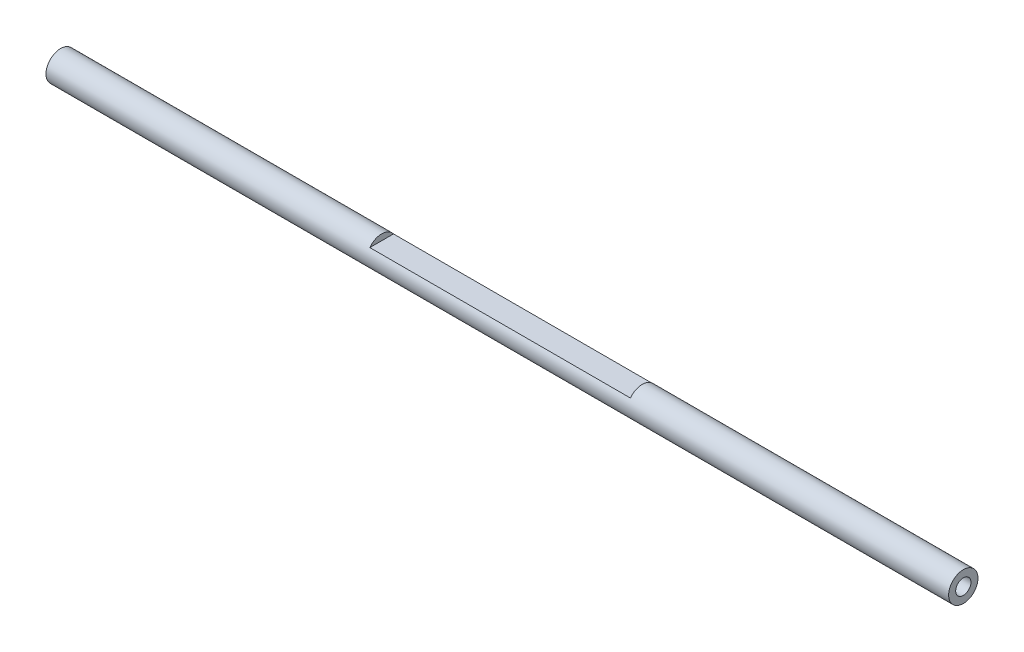
SolidWorks part; units mm, degrees
ref_plane "Front Plane" through (0, 0, 0) normal (0, 0, 1) x (1, 0, 0)
ref_plane "Top Plane" through (0, 0, 0) normal (0, 1, 0) x (1, 0, 0)
ref_plane "Right Plane" through (0, 0, 0) normal (1, 0, 0) x (0, 0, -1)
sketch "Sketch1" plane through (0, 0, 0) normal (1, 0, 0) x (0, 0, -1)
  line L1 (10, 8.45) -> (-10, 8.45)
  line L2 (10, 8.45) -> (10, -8.45)
  line L3 (10, -8.45) -> (-10, -8.45)
  line L4 (-10, 8.45) -> (-10, -8.45)
  line L5 (10, 8.45) -> (-10, -8.45) construction
  line L6 (10, -8.45) -> (-10, 8.45) construction
  circle A0 centre (0, 0) radius 8.45 construction
  point P0 (0, 0)
  dimension "D1" = 16.9
  dimension "D2" = 20
extrude "Boss-Extrude1" add sketch "Sketch1" along normal mid plane 47.5
sketch "Sketch2" plane through (23.75, 0, 0) normal (1, 0, 0) x (0, 0, -1)
  circle A0 centre (0, 0) radius 8.45
  dimension "D1" = 16.9
extrude "Boss-Extrude2" add sketch "Sketch2" along normal blind 236
hole_wizard "M10x1.25 Tapped Hole1" positions "3DSketch1" profile "Sketch3" tap size "M10x1.25" standard "DIN"
sketch3d "3DSketch1"
  point P0 (259.75, 0, 0)
sketch "Sketch3" plane through (259.75, 0, 0) normal (0, 1, 0) x (0, 0, -1)
  line L0 (0, 0) -> (0, 32.6438)
  line L1 (0, 32.6438) -> (4.4, 30)
  line L2 (4.4, 30) -> (4.4, 0)
  line L5 (4.4, 0) -> (0, 0)
  line L10 (0, 32.6438) -> (-4.4, 30) construction
  line L11 (0, -6.35) -> (0, 107.95) construction
  dimension "Tap Drill Dia." = 8.8
  dimension "Tap Drill Depth" = 30
  dimension "Drill Angle" = 118
mirror "Mirror1" about plane through (0, 0, 0) normal (1, 0, 0) of "Boss-Extrude2", "M10x1.25 Tapped Hole1"
sketch "Sketch5" plane through (0, 0, 0) normal (0, 1, 0) x (1, 0, 0)
  line L0 (0, 94.6683) -> (0, -76.9789) construction
  line L1 (-259.75, 8.45) -> (-259.75, -8.45) construction
  point P0 (-253.5, 0)
  point P6 (253.5, 0)
  dimension "D1" = 6.25
sketch "Sketch6" plane through (0, 0, 0) normal (1, 0, 0) x (0, 0, -1)
  circle A0 centre (0, 0) radius 8.45
  dimension "D1" = 16.9
extrude "Cut-Extrude-Thin1" cut sketch "Sketch6" against normal mid plane 60 thin
sketch "Sketch7" plane through (0, 0, 0) normal (0, 1, 0) x (1, 0, 0)
  line L1 (75, 20) -> (-75, 20)
  line L2 (75, 20) -> (75, -20)
  line L3 (75, -20) -> (-75, -20)
  line L4 (-75, 20) -> (-75, -20)
  line L5 (75, 20) -> (-75, -20) construction
  line L6 (75, -20) -> (-75, 20) construction
  point P0 (0, 0)
  dimension "D1" = 150
  dimension "D2" = 40
extrude "Cut-Extrude1" cut sketch "Sketch7" along normal blind 10 from offset 5
sketch3d "3DSketch2"
  line L0 (-253.5, 0, 0) -> (253.5, 0, 0) construction
  line L1 (253.5, 0, 0) -> (285.75, 0, 0)
  line L2 (-253.5, 0, 0) -> (-285.75, 0, 0)
sketch3d "3DSketch3"
  point P1 (0, 0, 0)
